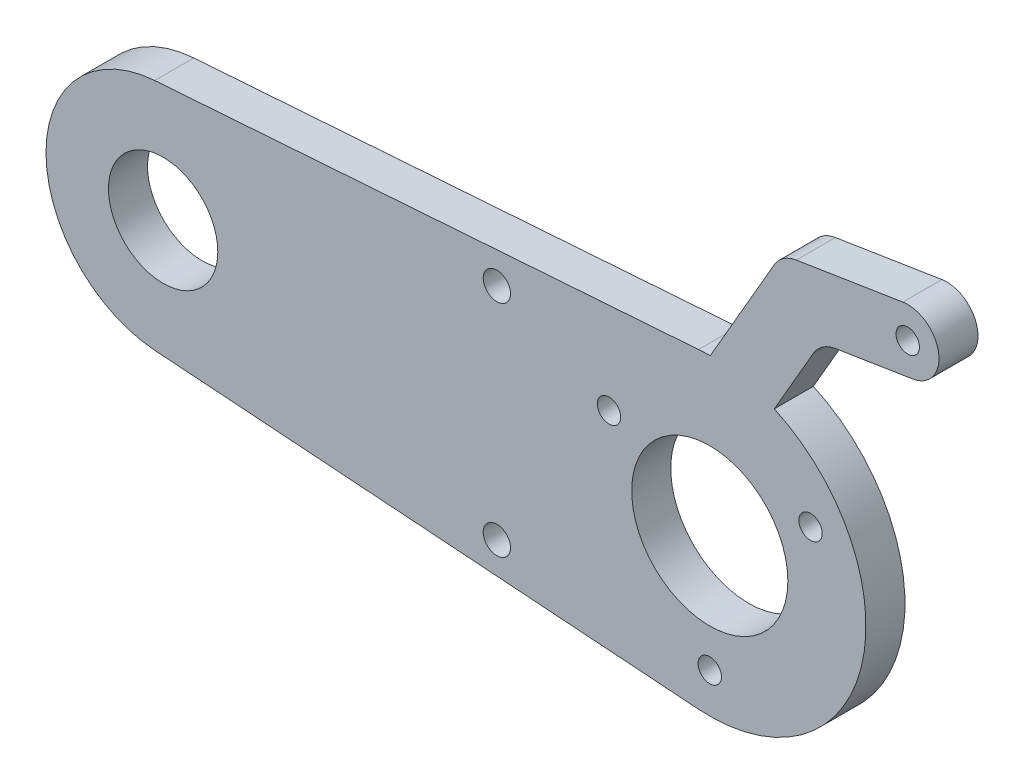
SolidWorks part; units mm, degrees
ref_plane "Front Plane" through (0, 0, 0) normal (0, 0, 1) x (1, 0, 0)
ref_plane "Top Plane" through (0, 0, 0) normal (0, 1, 0) x (1, 0, 0)
ref_plane "Right Plane" through (0, 0, 0) normal (1, 0, 0) x (0, 0, -1)
sketch "Sketch1" plane through (0, 0, 0) normal (0, 0, 1) x (1, 0, 0)
  line L0 (-71.0714, 14.9617) -> (-1.4286, 19.9489)
  line L1 (-71.0714, -14.9617) -> (-1.4286, -19.9489)
  line L2 (8.243, 34.178) -> (0.0573, 19.9999)
  line L3 (11.0813, 36.1287) -> (24.7271, 38.29)
  line L5 (25.9785, 30.3885) -> (16.1016, 28.8241)
  line L6 (13.2633, 26.8734) -> (8.2633, 18.2131)
  line L7 (0, 0) -> (0, 20.1614) construction
  arc A0 (-1.4286, -19.9489) -> (-1.4286, 19.9489) centre (0, 0) ccw construction
  arc A1 (-71.0714, -14.9617) -> (-71.0714, 14.9617) centre (-70, 0) cw
  circle A3 centre (-70, 0) radius 7
  circle A4 centre (0, 0) radius 10
  circle A5 centre (-12.9038, 7.45) radius 1.5
  circle A6 centre (0, -14.9) radius 1.5
  arc A10 (0.0573, 19.9999) -> (-1.4286, 19.9489) centre (0, 0) ccw
  arc A11 (8.2633, 18.2131) -> (-1.4286, -19.9489) centre (0, 0) cw
  arc A12 (25.9785, 30.3885) -> (24.7271, 38.29) centre (25.3528, 34.3392) ccw
  circle A16 centre (-27.2623, 14.0887) radius 1.75
  circle A17 centre (-27.2623, -14.0887) radius 1.75
  circle A18 centre (12.9038, 7.45) radius 1.5
  arc A19 (8.243, 34.178) -> (11.0813, 36.1287) centre (11.7071, 32.178) cw
  arc A20 (16.1016, 28.8241) -> (13.2633, 26.8734) centre (16.7274, 24.8734) ccw
  circle A21 centre (25.3528, 34.3392) radius 1.5
  point P9 (-85, 0)
  dimension "D2" = 20
  dimension "D3" = 15
  dimension "D6" = 3
  dimension "D7" = 14
  dimension "D10" = 3.5
  dimension "D13" = 3.5
  dimension "D5" = 3
  dimension "D4" = 20
  dimension "D9" = 3
  dimension "D16" = 8
  dimension "D17" = 8
  dimension "D18" = 4
  dimension "D19" = 3
  dimension "D1" = 70
  dimension "D8" = 15
  dimension "D11" = 4
  dimension "D12" = 45
  dimension "D14" = 4
  dimension "D15" = 45
  dimension "D20" = 10
  dimension "D21" = 10
  dimension "D22" = 30
  dimension "D23" = 129
extrude "Boss-Extrude1" add sketch "Sketch1" along normal blind 5
